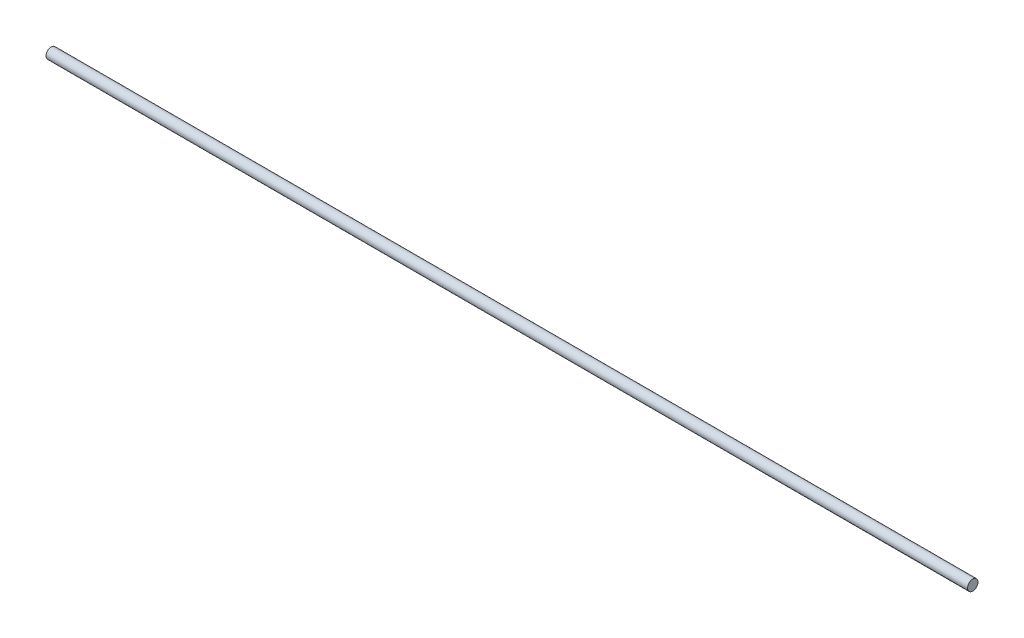
SolidWorks part; units mm, degrees
ref_plane "Front Plane" through (0, 0, 0) normal (0, 0, 1) x (1, 0, 0)
ref_plane "Top Plane" through (0, 0, 0) normal (0, 1, 0) x (1, 0, 0)
ref_plane "Right Plane" through (0, 0, 0) normal (1, 0, 0) x (0, 0, -1)
sketch "Sketch1" plane through (0, 0, 0) normal (1, 0, 0) x (0, 0, -1)
  circle A0 centre (0, 0) radius 4
  dimension "D1" = 8
extrude "Boss-Extrude1" add sketch "Sketch1" along normal blind 705
